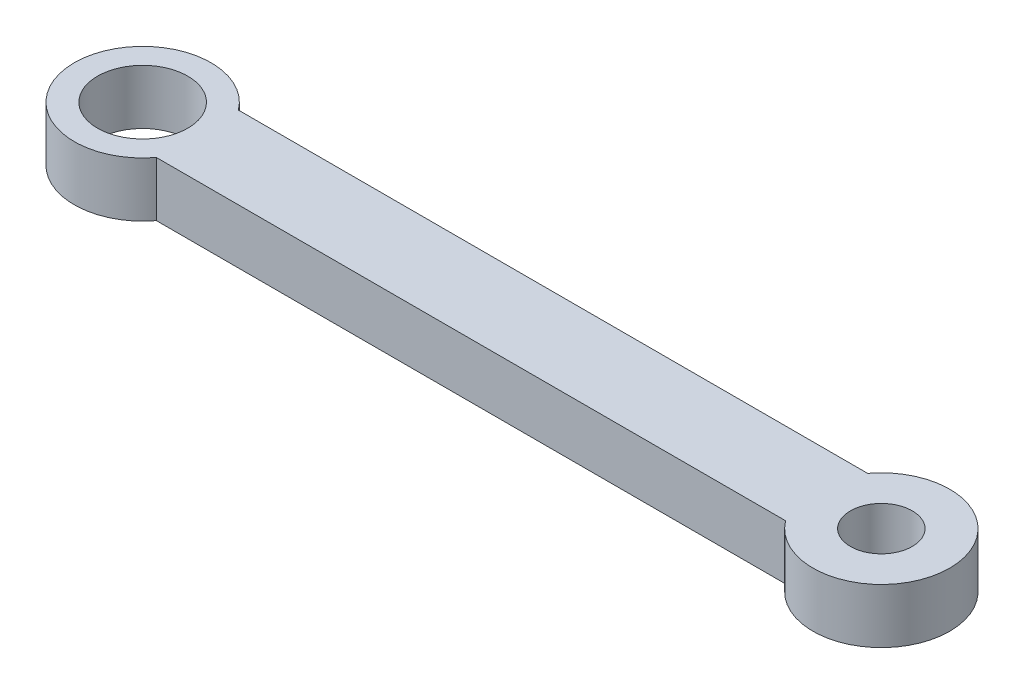
SolidWorks part; units mm, degrees
ref_plane "Front Plane" through (0, 0, 0) normal (0, 0, 1) x (1, 0, 0)
ref_plane "Top Plane" through (0, 0, 0) normal (0, 1, 0) x (1, 0, 0)
ref_plane "Right Plane" through (0, 0, 0) normal (1, 0, 0) x (0, 0, -1)
sketch "Sketch1" plane through (0, 0, 0) normal (0, 1, 0) x (1, 0, 0)
  line L0 (-11.5, 1.5) -> (11.5, 1.5)
  line L1 (-13.5, -1.5) -> (13.5, -1.5) construction
  line L2 (-13.5, -1.5) -> (-13.5, 1.5) construction
  line L3 (-13.5, 1.5) -> (13.5, 1.5) construction
  line L4 (13.5, -1.5) -> (13.5, 1.5) construction
  line L5 (-13.5, -1.5) -> (13.5, 1.5) construction
  line L6 (-13.5, 1.5) -> (13.5, -1.5) construction
  line L7 (-11.5, -1.5) -> (11.5, -1.5)
  circle A0 centre (-13.5, 0) radius 2.5 construction
  circle A1 centre (13.5, 0) radius 2.5 construction
  arc A2 (-11.5, 1.5) -> (-11.5, -1.5) centre (-13.5, 0) ccw
  arc A3 (11.5, 1.5) -> (11.5, -1.5) centre (13.5, 0) cw
  circle A4 centre (-13.5, 0) radius 1.65
  circle A5 centre (13.5, 0) radius 1.1303
  point P0 (0, 0)
  dimension "D3" = 5
  dimension "D4" = 3.3
  dimension "D5" = 2.2606
  dimension "D1" = 27
  dimension "D2" = 3
extrude "Boss-Extrude1" add sketch "Sketch1" along normal blind 2
